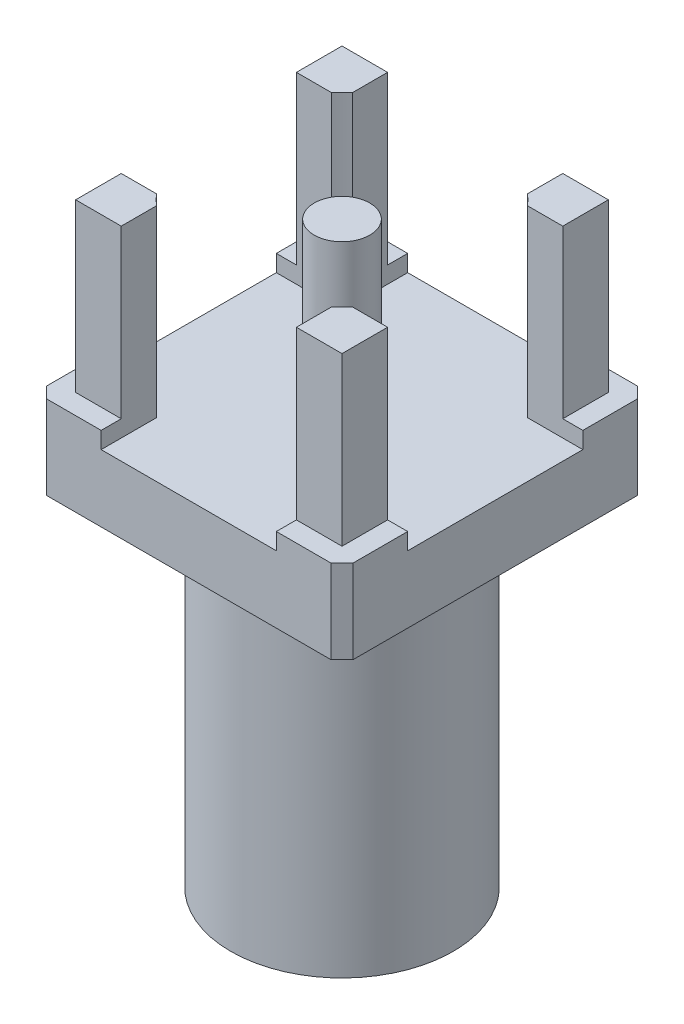
SolidWorks part; units mm, degrees
material "Brass"
ref_plane "Front Plane" through (0, 0, 0) normal (0, 0, 1) x (1, 0, 0)
ref_plane "Top Plane" through (0, 0, 0) normal (0, 1, 0) x (1, 0, 0)
ref_plane "Right Plane" through (0, 0, 0) normal (1, 0, 0) x (0, 0, -1)
sketch "Sketch1" plane through (0, 0, 0) normal (0, 1, 0) x (1, 0, 0)
  line L1 (-3.5, -3.5) -> (3.5, -3.5)
  line L2 (-3.5, -3.5) -> (-3.5, 3.5)
  line L3 (-3.5, 3.5) -> (3.5, 3.5)
  line L4 (3.5, -3.5) -> (3.5, 3.5)
  line L5 (-3.5, -3.5) -> (3.5, 3.5) construction
  line L6 (-3.5, 3.5) -> (3.5, -3.5) construction
  point P0 (0, 0)
  dimension "D1" = 7
extrude "Boss-Extrude1" add sketch "Sketch1" along normal blind 1.53
sketch "Sketch2" plane through (0, 0, 0) normal (0, -1, 0) x (1, 0, 0)
  circle A0 centre (0, 0) radius 2.54
  dimension "D1" = 5.08
extrude "Boss-Extrude2" add sketch "Sketch2" along normal blind 7.874
sketch "Sketch3" plane through (0, 1.53, 0) normal (0, 1, 0) x (1, 0, 0)
  circle A0 centre (0, 0) radius 0.635
  dimension "D1" = 1.27
extrude "Boss-Extrude3" add sketch "Sketch3" along normal blind 3.81
chamfer "Chamfer1" distance 0.25 4 edges at (-3.5, 0.765, 3.5) (3.5, 0.765, 3.5) (3.5, 0.765, -3.5) (-3.5, 0.765, -3.5)
sketch "Sketch4" plane through (0, 1.53, 0) normal (0, 1, 0) x (1, 0, 0)
  line L0 (-3.5, 2) -> (-2, 2)
  line L1 (-3.5, 3.25) -> (-3.5, -3.25) construction
  line L2 (-2, 2) -> (-2, 3.5)
  line L3 (3.25, 3.5) -> (-3.25, 3.5) construction
  line L4 (-2, 3.5) -> (-3.25, 3.5)
  line L5 (-3.25, 3.5) -> (-3.5, 3.25)
  line L6 (-3.5, 3.25) -> (-3.5, 2)
  line L7 (0, 0) -> (0, 3.5) construction
  line L8 (0, 0) -> (-3.5, 0) construction
  line L9 (3.5, 3.25) -> (3.5, 2)
  line L10 (3.25, 3.5) -> (3.5, 3.25)
  line L11 (2, 3.5) -> (3.25, 3.5)
  line L12 (2, 2) -> (2, 3.5)
  line L13 (3.5, 2) -> (2, 2)
  line L14 (3.5, -2) -> (2, -2)
  line L15 (2, -2) -> (2, -3.5)
  line L16 (2, -3.5) -> (3.25, -3.5)
  line L17 (3.25, -3.5) -> (3.5, -3.25)
  line L18 (3.5, -3.25) -> (3.5, -2)
  line L19 (-3.5, -3.25) -> (-3.5, -2)
  line L20 (-3.25, -3.5) -> (-3.5, -3.25)
  line L21 (-2, -3.5) -> (-3.25, -3.5)
  line L22 (-2, -2) -> (-2, -3.5)
  line L23 (-3.5, -2) -> (-2, -2)
  dimension "D1" = 1.5
extrude "Boss-Extrude4" add sketch "Sketch4" along normal blind 0.381
sketch "Sketch5" plane through (0, 1.911, 0) normal (0, 1, 0) x (1, 0, 0)
  line L0 (0, 0) -> (0, 3.5) construction
  line L1 (-2, 2) -> (-3.0414, 2)
  line L2 (-2, 2) -> (-2, 3.0414)
  line L3 (-2, 3.0414) -> (-3.0414, 3.0414)
  line L4 (-3.0414, 2) -> (-3.0414, 3.0414)
  line L5 (0, 0) -> (-3.5, 0) construction
  line L6 (-3.5, 2) -> (-3.5, -2) construction
  line L7 (2, 3.5) -> (-2, 3.5) construction
  line L8 (3.0414, 2) -> (3.0414, 3.0414)
  line L9 (2, 3.0414) -> (3.0414, 3.0414)
  line L10 (2, 2) -> (2, 3.0414)
  line L11 (2, 2) -> (3.0414, 2)
  line L12 (2, -2) -> (3.0414, -2)
  line L13 (2, -2) -> (2, -3.0414)
  line L14 (2, -3.0414) -> (3.0414, -3.0414)
  line L15 (3.0414, -2) -> (3.0414, -3.0414)
  line L16 (-3.0414, -2) -> (-3.0414, -3.0414)
  line L17 (-2, -3.0414) -> (-3.0414, -3.0414)
  line L18 (-2, -2) -> (-2, -3.0414)
  line L19 (-2, -2) -> (-3.0414, -2)
  dimension "D1" = 1.0414
extrude "Boss-Extrude5" add sketch "Sketch5" along normal blind 3.81
sketch "Sketch6" plane through (0, 5.721, 0) normal (0, 1, 0) x (1, 0, 0)
  circle A0 centre (0, 0) radius 3
  circle A1 centre (0, 0) radius 2.55
  dimension "D1" = 6
  dimension "D2" = 0.45
extrude "File To Fit" cut sketch "Sketch6" against normal up to surface (4.191 mm away) up to face at (0, 1.53, -0.635)
